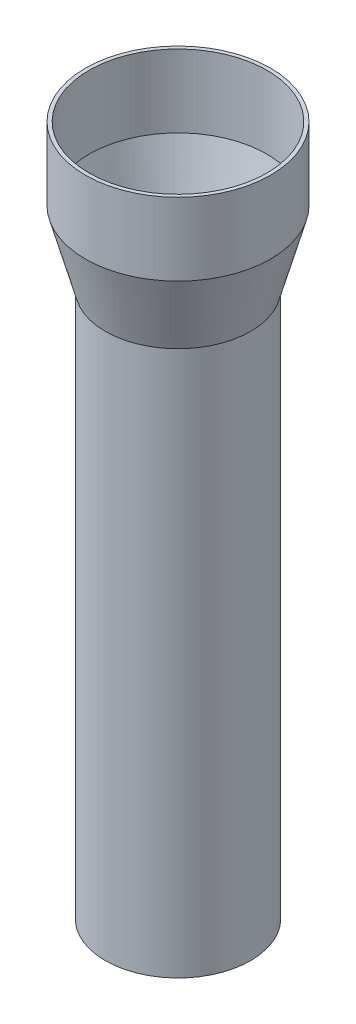
SolidWorks part; units mm, degrees
ref_plane "Front Plane" through (0, 0, 0) normal (0, 0, 1) x (1, 0, 0)
ref_plane "Top Plane" through (0, 0, 0) normal (0, 1, 0) x (1, 0, 0)
ref_plane "Right Plane" through (0, 0, 0) normal (1, 0, 0) x (0, 0, -1)
sketch "Sketch1" plane through (0, 0, 0) normal (0, 1, 0) x (1, 0, 0)
  circle A0 centre (0, 0) radius 10
  dimension "D1" = 20
extrude "Boss-Extrude1" add sketch "Sketch1" along normal blind 75
sketch "Sketch2" plane through (0, 75, 0) normal (0, 1, 0) x (1, 0, 0)
  circle A0 centre (0, 0) radius 9.5
  dimension "D1" = 19
extrude "Cut-Extrude1" cut sketch "Sketch2" against normal through all
sketch "Sketch3" plane through (0, 0, 0) normal (1, 0, 0) x (0, 0, -1)
  line L0 (10, 75) -> (12.75, 85)
  line L1 (9.5, 75) -> (12.25, 85)
  line L2 (12.25, 85) -> (12.75, 85)
  line L3 (9.5, 75) -> (10, 75)
  dimension "D1" = 2.75
  dimension "D2" = 10
  dimension "D3" = 2.75
  dimension "D4" = 10
ref_axis "Axis1" through (0, 75, 0) along (0, -1, 0)
revolve "Revolve1" add sketch "Sketch3" angle 360 about axis through (0, 75, 0) along (0, -1, 0)
sketch "Sketch4" plane through (0, 0, 0) normal (1, 0, 0) x (0, 0, -1)
  line L0 (12.75, 85) -> (12.75, 95)
  line L1 (12.25, 85) -> (12.25, 95)
  line L2 (12.25, 95) -> (12.75, 95)
  line L3 (12.75, 85) -> (12.25, 85)
  dimension "D1" = 10
revolve "Revolve2" add sketch "Sketch4" angle 360 about axis through (0, 75, 0) along (0, -1, 0)
